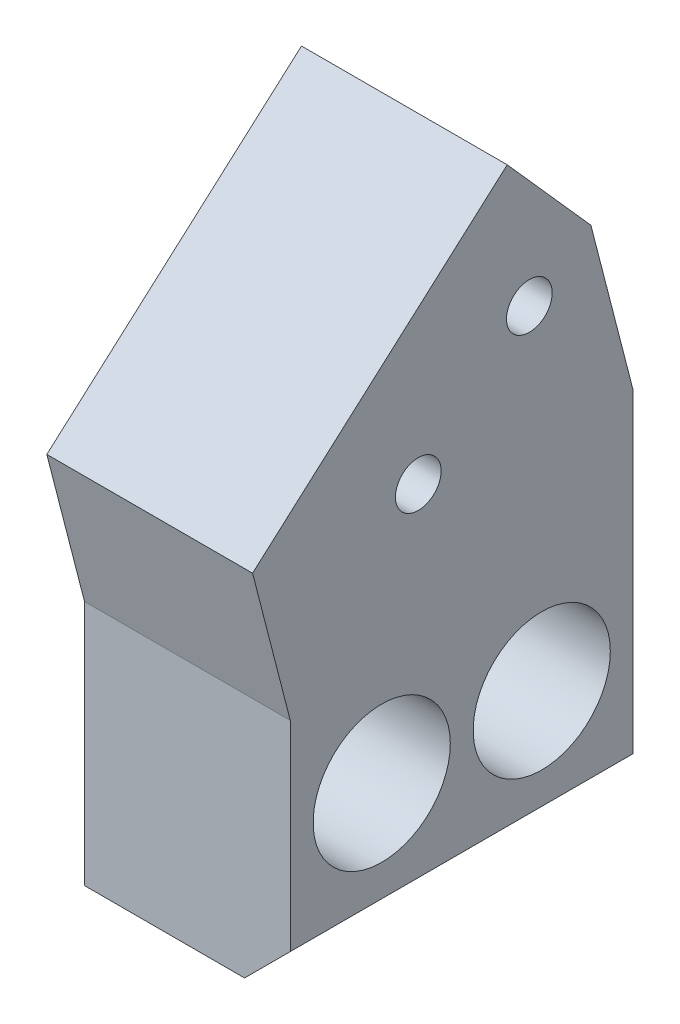
SolidWorks part; units mm, degrees
ref_plane "Front Plane" through (0, 0, 0) normal (0, 0, 1) x (1, 0, 0)
ref_plane "Top Plane" through (0, 0, 0) normal (0, 1, 0) x (1, 0, 0)
ref_plane "Right Plane" through (0, 0, 0) normal (1, 0, 0) x (0, 0, -1)
sketch "Sketch1" plane through (0, 0, 0) normal (1, 0, 0) x (0, 0, -1)
  line L0 (-7.5, 0) -> (7.5, 0)
  line L1 (7.5, 0) -> (7.5, 15.76)
  line L2 (-7.5, 0) -> (-7.5, 10.76)
  line L3 (-7.5, 10.76) -> (-9.1494, 17.1609)
  line L4 (7.5, 15.76) -> (4.1038, 28.9395)
  line L5 (-9.1494, 17.1609) -> (4.1038, 28.9395)
  line L6 (-7.7469, 11.7181) -> (5.5064, 23.4967) construction
  circle A0 centre (2.9575, 21.2314) radius 1
  circle A1 centre (-1.9011, 16.9135) radius 1
  point P4 (0, 0)
  dimension "D7" = 5
  dimension "D8" = 2
  dimension "D9" = 3.41
  dimension "D10" = 6.5
  dimension "D1" = 15
  dimension "D2" = 15.76
  dimension "D3" = 10.76
  dimension "D4" = 194.45
  dimension "D5" = 6.61
  dimension "D6" = 13.61
extrude "Boss-Extrude1" add sketch "Sketch1" along normal blind 9
chamfer "Chamfer1" distance 2 angle 45 2 edges at (9, 0, 0) (4.5, 0, -7.5)
sketch "Sketch4" plane through (9, 0, 0) normal (1, 0, 0) x (0, 0, -1)
sketch "Sketch5" plane through (9, 0, 0) normal (1, 0, 0) x (0, 0, -1)
  circle A0 centre (3.5, 6.38) radius 1.411
  circle A1 centre (-3.5, 6.38) radius 1.411
  point P6 (0, 0)
  point P7 (0, 0)
extrude "Cut-Extrude4" cut sketch "Sketch5" against normal through all
sketch "Sketch6" plane through (9, 0, 0) normal (1, 0, 0) x (0, 0, -1)
  line L0 (1.9905, 27.0613) -> (5.6484, 22.9455)
  line L1 (4.1038, 28.9395) -> (-9.1494, 17.1609) construction
  line L2 (4.4484, 24.2957) -> (1.9905, 27.0613) construction
  line L3 (7.5, 15.76) -> (4.1038, 28.9395) construction
  line L4 (6.1092, 22.427) -> (4.4484, 24.2957) construction
  line L5 (5.6484, 22.9455) -> (4.1038, 28.9395)
  line L6 (4.1038, 28.9395) -> (1.9905, 27.0613)
extrude "Cut-Extrude5" cut sketch "Sketch6" against normal through all
sketch "Sketch7" plane through (9, 0, 0) normal (1, 0, 0) x (0, 0, -1)
  circle A0 centre (3.5, 6.38) radius 3
  circle A1 centre (-3.5, 6.38) radius 3
  point P6 (0, 0)
  point P7 (0, 0)
  dimension "D1" = 6
extrude "Cut-Extrude6" cut sketch "Sketch7" against normal blind 5 contours A0 | A1
